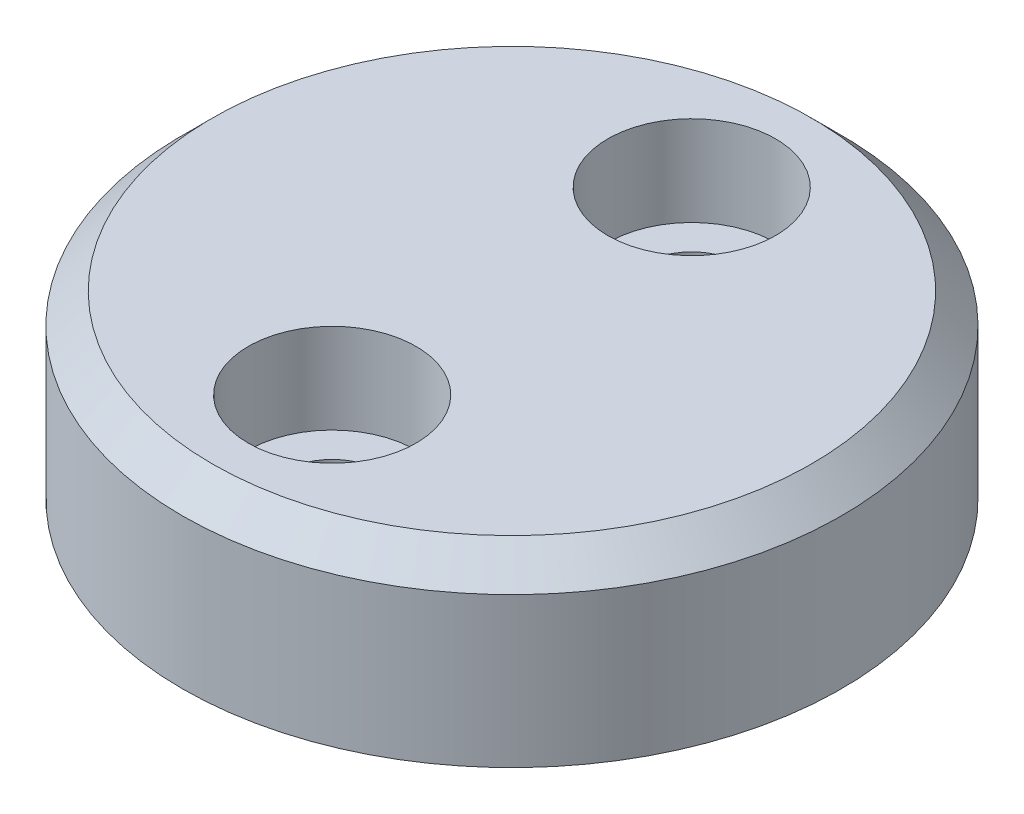
SolidWorks part; units mm, degrees
ref_plane "Plan de face" through (0, 0, 0) normal (0, 0, 1) x (1, 0, 0)
ref_plane "Plan de dessus" through (0, 0, 0) normal (0, 1, 0) x (1, 0, 0)
ref_plane "Plan de droite" through (0, 0, 0) normal (1, 0, 0) x (0, 0, -1)
sketch "Esquisse1" plane through (0, 0, 0) normal (0, 1, 0) x (1, 0, 0)
  circle A0 centre (0, 0) radius 10
  dimension "D1" = 20
extrude "Boss.-Extru.1" add sketch "Esquisse1" along normal blind 0.5
sketch "Esquisse2" plane through (0, 0.5, 0) normal (0, 1, 0) x (1, 0, 0)
  circle A0 centre (0, 0) radius 11
  dimension "D1" = 22
extrude "Boss.-Extru.2" add sketch "Esquisse2" along normal blind 6
chamfer "Chanfrein1" distance 1 angle 45 1 edges at (0, 6.5, 11)
sketch "Esquisse3" plane through (0, 6.5, 0) normal (0, 1, 0) x (1, 0, 0)
  circle A0 centre (0, 0) radius 6 construction
  circle A1 centre (0, 6) radius 1.6
  circle A2 centre (0, -6) radius 1.6
  point P5 (0, -6)
  dimension "D1" = 3.2
  dimension "D2" = 12
  dimension "D3" = 2
extrude "Enlèv. mat.-Extru.1" cut sketch "Esquisse3" against normal through all
sketch "Esquisse4" plane through (0, 6.5, 0) normal (0, 1, 0) x (1, 0, 0)
  circle A0 centre (0, 6) radius 2.8
  circle A1 centre (0, -6) radius 2.8
  dimension "D1" = 5.6
extrude "Enlèv. mat.-Extru.2" cut sketch "Esquisse4" against normal blind 3
